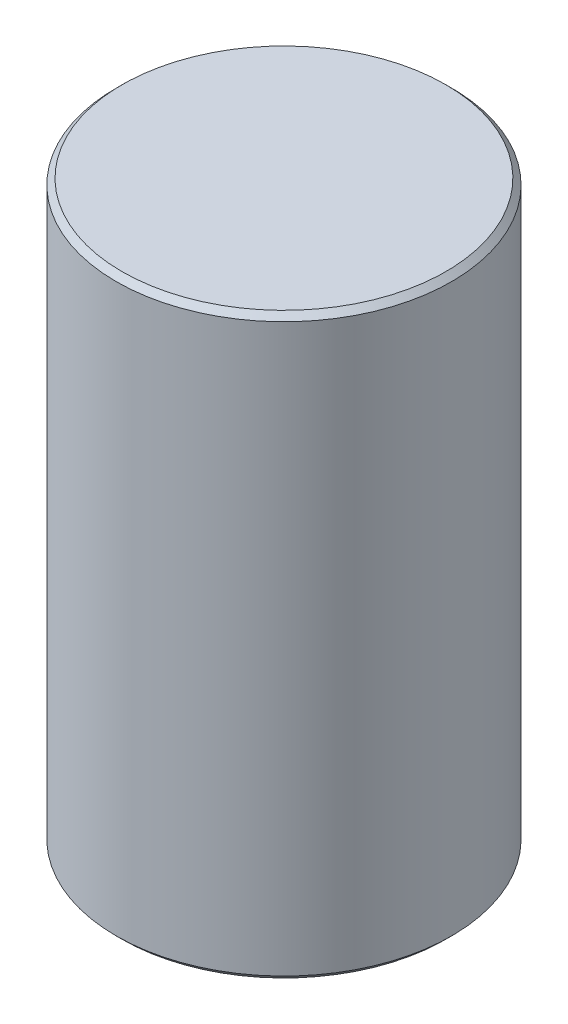
SolidWorks part; units mm, degrees
ref_plane "Front Plane" through (0, 0, 0) normal (0, 0, 1) x (1, 0, 0)
ref_plane "Top Plane" through (0, 0, 0) normal (0, 1, 0) x (1, 0, 0)
ref_plane "Right Plane" through (0, 0, 0) normal (1, 0, 0) x (0, 0, -1)
sketch "Sketch1" plane through (0, 0, 0) normal (0, 1, 0) x (1, 0, 0)
  circle A0 centre (0, 0) radius 14.5
  dimension "D1" = 29
extrude "Boss-Extrude1" add sketch "Sketch1" along normal blind 50
sketch "Sketch2" plane through (0, 0, 0) normal (0, -1, 0) x (1, 0, 0)
  line L1 (-12.75, -0.9) -> (12.75, -0.9)
  line L2 (-12.75, -0.9) -> (-12.75, 0.9)
  line L3 (-12.75, 0.9) -> (12.75, 0.9)
  line L4 (12.75, -0.9) -> (12.75, 0.9)
  line L5 (-12.75, -0.9) -> (12.75, 0.9) construction
  line L6 (-12.75, 0.9) -> (12.75, -0.9) construction
  circle A0 centre (0, 0) radius 12.7817
  circle A1 centre (-14.5, 0) radius 3
  circle A2 centre (0, 0) radius 14.5 construction
  circle A3 centre (14.5, 0) radius 3
  circle A4 centre (0, 12.7817) radius 3
  circle A5 centre (0, -12.7817) radius 3
  circle A6 centre (0, 12.7817) radius 1.1
  circle A7 centre (0, -12.7817) radius 1.1
  point P0 (0, 0)
  dimension "D3" = 6
  dimension "D4" = 6
  dimension "D5" = 6
  dimension "D6" = 6
  dimension "D7" = 2.2
  dimension "D8" = 2.2
  dimension "D1" = 1.8
  dimension "D2" = 25.5
extrude "Cut-Extrude1" cut sketch "Sketch2" against normal blind 47 contours L1 A1 L3 L2 | A3 L3 A1 L1 | L3 A3 L1 L4 | A3 A0 A1 L3 | A3 L1 A1 A0 | A6 | A7
chamfer "Chamfer1" distance 0.5 angle 45 10 edges at (-9.2804, 47, -8.789) (9.2804, 47, 8.789) (12.75, 47, 0) (-12.75, 47, 0) (-9.2804, 0, 8.789) (9.2804, 0, 8.789) (9.2804, 0, -8.789) (-9.2804, 0, -8.789) (0, 0, 14.5) (0, 50, 14.5)
